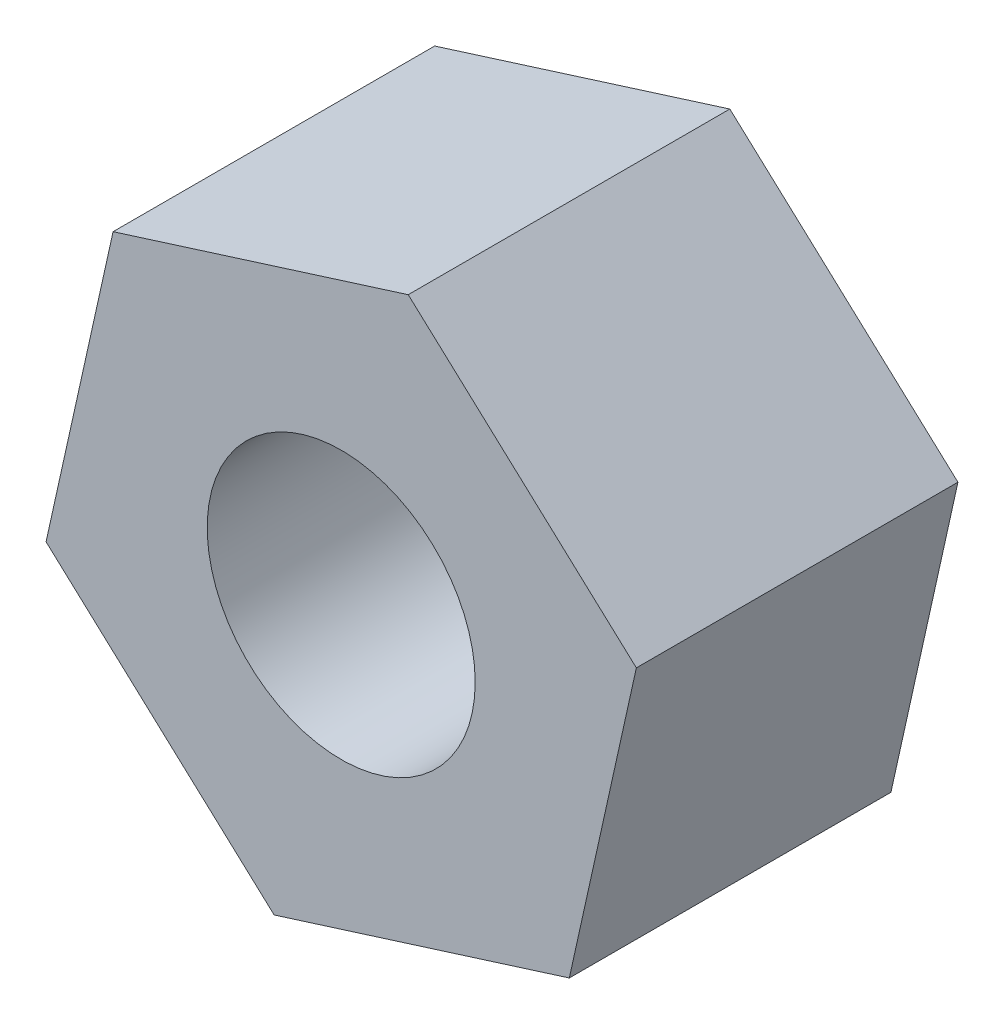
SolidWorks part; units mm, degrees
ref_plane "正面" through (0, 0, 0) normal (0, 0, 1) x (1, 0, 0)
ref_plane "平面" through (0, 0, 0) normal (0, 1, 0) x (1, 0, 0)
ref_plane "右側面" through (0, 0, 0) normal (1, 0, 0) x (0, 0, -1)
sketch "ｽｹｯﾁ1" plane through (0, 0, 0) normal (0, 0, 1) x (1, 0, 0)
  line L1 (4.256, -3.9013) -> (5.5066, 1.7351)
  line L2 (5.5066, 1.7351) -> (1.2506, 5.6364)
  line L3 (1.2506, 5.6364) -> (-4.256, 3.9013)
  line L4 (-4.256, 3.9013) -> (-5.5066, -1.7351)
  line L5 (-5.5066, -1.7351) -> (-1.2506, -5.6364)
  line L6 (-1.2506, -5.6364) -> (4.256, -3.9013)
  circle A0 centre (0, 0) radius 5 construction
  dimension "D1" = 10
extrude "ﾎﾞｽ - 押し出し1" add sketch "ｽｹｯﾁ1" along normal blind 6
sketch "ｽｹｯﾁ2" plane through (0, 0, 6) normal (0, 0, 1) x (1, 0, 0)
  circle A0 centre (0, 0) radius 2.5
  dimension "D1" = 5
extrude "ｶｯﾄ - 押し出し1" cut sketch "ｽｹｯﾁ2" against normal through all
